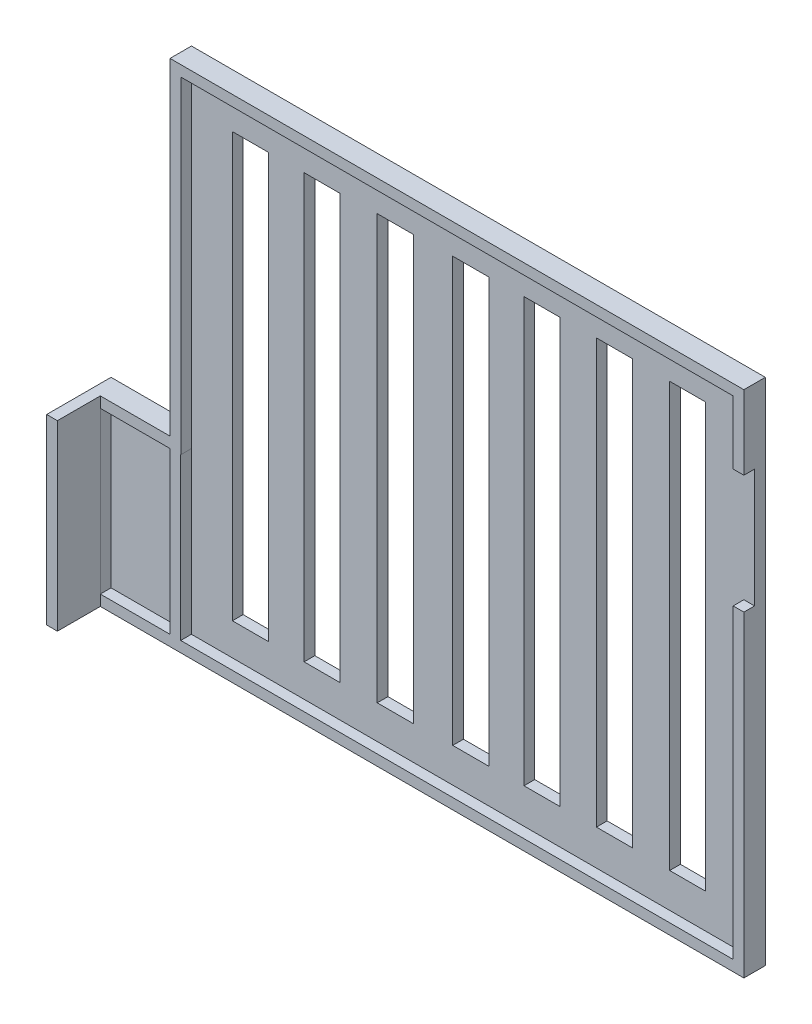
SolidWorks part; units mm, degrees
ref_plane "Front Plane" through (0, 0, 0) normal (0, 0, 1) x (1, 0, 0)
ref_plane "Top Plane" through (0, 0, 0) normal (0, 1, 0) x (1, 0, 0)
ref_plane "Right Plane" through (0, 0, 0) normal (1, 0, 0) x (0, 0, -1)
sketch "Sketch1" plane through (0, 0, 0) normal (0, 0, 1) x (1, 0, 0)
  line L0 (-30.6875, 30.8414) -> (-23.9701, 30.8414)
  line L1 (-53.6886, 38.7896) -> (53.3114, 38.7896)
  line L2 (-53.6886, 38.7896) -> (-53.6886, -56.2104)
  line L3 (-53.6886, -56.2104) -> (53.3114, -56.2104)
  line L4 (53.3114, 38.7896) -> (53.3114, -56.2104)
  line L5 (-53.6886, -56.2104) -> (-68.6886, -56.2104)
  line L6 (-53.6886, -56.2104) -> (-53.6886, -22.2104)
  line L7 (-53.6886, -22.2104) -> (-68.6886, -22.2104)
  line L8 (-68.6886, -56.2104) -> (-68.6886, -22.2104)
  line L9 (-44.0582, 30.7896) -> (-37.3408, 30.7896)
  line L10 (-44.0582, 30.7896) -> (-44.0582, -48.2104)
  line L11 (-44.0582, -48.2104) -> (-37.3408, -48.2104)
  line L12 (-37.3408, 30.7896) -> (-37.3408, -48.2104)
  line L13 (-30.6875, 30.8414) -> (-30.6875, -48.1586)
  line L14 (-30.6875, -48.1586) -> (-23.9701, -48.1586)
  line L15 (-23.9701, 30.8414) -> (-23.9701, -48.1586)
  line L16 (-17.0516, 31.0424) -> (-10.3342, 31.0424)
  line L17 (-17.0516, 31.0424) -> (-17.0516, -47.9576)
  line L18 (-17.0516, -47.9576) -> (-10.3342, -47.9576)
  line L19 (-10.3342, 31.0424) -> (-10.3342, -47.9576)
  line L20 (-2.9762, 31.2056) -> (3.7412, 31.2056)
  line L21 (-2.9762, 31.2056) -> (-2.9762, -47.7944)
  line L22 (-2.9762, -47.7944) -> (3.7412, -47.7944)
  line L23 (3.7412, 31.2056) -> (3.7412, -47.7944)
  line L24 (10.3141, 31.3338) -> (17.0315, 31.3338)
  line L25 (10.3141, 31.3338) -> (10.3141, -47.6662)
  line L26 (10.3141, -47.6662) -> (17.0315, -47.6662)
  line L27 (17.0315, 31.3338) -> (17.0315, -47.6662)
  line L28 (23.8188, 31.4097) -> (30.5362, 31.4097)
  line L29 (23.8188, 31.4097) -> (23.8188, -47.5903)
  line L30 (23.8188, -47.5903) -> (30.5362, -47.5903)
  line L31 (30.5362, 31.4097) -> (30.5362, -47.5903)
  line L32 (37.4815, 31.2334) -> (44.1988, 31.2334)
  line L33 (37.4815, 31.2334) -> (37.4815, -47.7666)
  line L34 (37.4815, -47.7666) -> (44.1988, -47.7666)
  line L35 (44.1988, 31.2334) -> (44.1988, -47.7666)
  dimension "D1" = 107
  dimension "D2" = 95
  dimension "D3" = 15
  dimension "D4" = 34
  dimension "D5" = 8
  dimension "D6" = 8
  dimension "D7" = 9.6304
extrude "Boss-Extrude1" add sketch "Sketch1" along normal blind 4 contours L4 L1 L2 L3 L9 L12 L11 L10 L0 L15 L14 L13 L16 L19 L18 L17 L20 L23 L22 L21 L24 L27 L26 L25 L28 L31 L30 L29 L32 L35 L34 L33 | L8 L5 L2 L7
sketch "Sketch3" plane through (0, 0, 4) normal (0, 0, 1) x (1, 0, 0)
  line L18 (51.3114, -54.2104) -> (51.3114, 36.7896)
  line L19 (51.3114, 36.7896) -> (-51.6886, 36.7896)
  line L20 (-51.6886, 36.7896) -> (-51.6886, -24.2104)
  line L21 (-51.6886, -24.2104) -> (-66.6886, -24.2104)
  line L22 (-66.6886, -24.2104) -> (-66.6886, -54.2104)
  line L23 (-66.6886, -54.2104) -> (51.3114, -54.2104)
  line L24 (51.3114, -54.2104) -> (51.3114, 36.7896)
  line L25 (51.3114, 36.7896) -> (-51.6886, 36.7896)
  line L26 (-51.6886, 36.7896) -> (-51.6886, -24.2104)
  line L27 (-51.6886, -24.2104) -> (-66.6886, -24.2104)
  line L28 (-66.6886, -24.2104) -> (-66.6886, -54.2104)
  line L29 (-66.6886, -54.2104) -> (51.3114, -54.2104)
  dimension "D1" = 2
extrude "Cut-Extrude1" cut sketch "Sketch3" against normal blind 2
sketch "Sketch5" plane through (0, 0, 4) normal (0, 0, 1) x (1, 0, 0)
  line L0 (-68.6886, -56.2104) -> (53.3114, -56.2104) construction
  line L1 (-68.6886, -22.2104) -> (-66.6878, -22.2104)
  line L2 (-68.6886, -22.2104) -> (-68.6886, -56.2104)
  line L3 (-68.6886, -56.2104) -> (-66.6878, -56.2104)
  line L4 (-66.6878, -22.2104) -> (-66.6878, -56.2104)
extrude "Boss-Extrude3" add sketch "Sketch5" along normal blind 8
sketch "Sketch6" plane through (0, 0, 4) normal (0, 0, 1) x (1, 0, 0)
  line L0 (51.3114, -54.2104) -> (51.3114, 36.7896) construction
  line L1 (51.3114, 24.9769) -> (53.3114, 24.9769)
  line L2 (51.3114, 24.9769) -> (51.3114, 2.8741)
  line L3 (51.3114, 2.8741) -> (53.3114, 2.8741)
  line L4 (53.3114, 24.9769) -> (53.3114, 2.8741)
  line L5 (53.3114, 38.7896) -> (53.3114, -56.2104) construction
extrude "Cut-Extrude2" cut sketch "Sketch6" against normal blind 2
sketch "Sketch7" plane through (0, -24.2104, 0) normal (0, -1, 0) x (1, 0, 0)
  line L0 (-51.6886, 4) -> (-66.6878, 4) construction
  line L1 (-53.6881, 4) -> (-51.699, 4)
  line L2 (-53.6881, 4) -> (-53.6881, 2)
  line L3 (-53.6881, 2) -> (-51.699, 2)
  line L4 (-51.699, 4) -> (-51.699, 2)
  line L5 (-51.6886, 2) -> (-66.6886, 2) construction
extrude "Boss-Extrude4" add sketch "Sketch7" along normal blind 30
